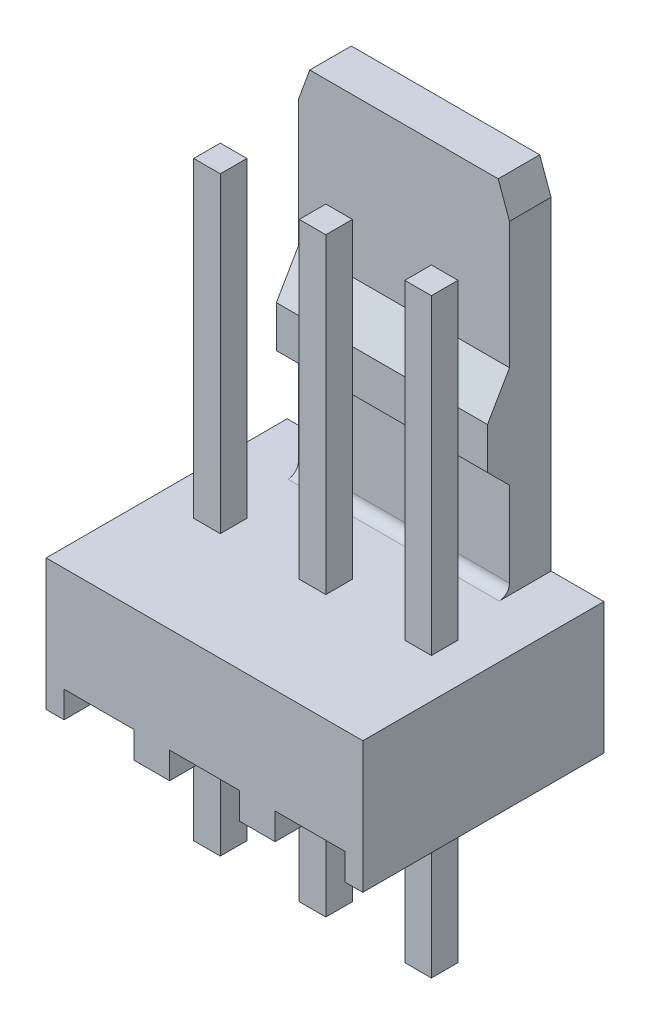
SolidWorks part; units mm, degrees
ref_plane "Front Plane" through (0, 0, 0) normal (0, 0, 1) x (1, 0, 0)
ref_plane "Top Plane" through (0, 0, 0) normal (0, 1, 0) x (1, 0, 0)
ref_plane "Right Plane" through (0, 0, 0) normal (1, 0, 0) x (0, 0, -1)
ref_plane "Plane1" through (0, -1.58, 0) normal (0, -1, 0) x (1, 0, 0)
sketch "Sketch1" plane through (0, -1.58, 0) normal (0, -1, 0) x (1, 0, 0)
  line L0 (3.81, -2.88) -> (3.81, 2.92)
  line L1 (3.81, 2.92) -> (-3.81, 2.92)
  line L2 (-3.81, 2.92) -> (-3.81, -2.88)
  line L3 (-3.81, -2.88) -> (3.81, -2.88)
extrude "Boss-Extrude1" add sketch "Sketch1" against normal blind 3.16
sketch "Sketch2" plane through (0, 1.58, 0) normal (0, 1, 0) x (-1, 0, 0)
  line L0 (2.54, -1.88) -> (2.54, -2.88)
  line L1 (2.54, -2.88) -> (-2.54, -2.88)
  line L2 (-2.54, -2.88) -> (-2.54, -1.88)
  line L3 (-2.54, -1.88) -> (2.54, -1.88)
extrude "Boss-Extrude2" add sketch "Sketch2" along normal blind 8.54
sketch "Sketch3" plane through (0, 0, -1.88) normal (0, 0, 1) x (1, 0, 0)
  line L0 (2.54, 10.12) -> (2.54, 3.87)
  line L1 (2.54, 3.87) -> (-2.54, 3.87)
  line L2 (-2.54, 3.87) -> (-2.54, 10.12)
  line L3 (-2.54, 10.12) -> (2.54, 10.12)
extrude "Boss-Extrude3" add sketch "Sketch3" along normal blind 0.53
sketch "Sketch4" plane through (0, 0, -2.88) normal (0, 0, -1) x (-1, 0, 0)
  line L0 (1.7, -1.58) -> (3.38, -1.58)
  line L1 (3.38, -1.58) -> (3.38, -0.94)
  line L2 (3.38, -0.94) -> (1.7, -0.94)
  line L3 (1.7, -0.94) -> (1.7, -1.58)
extrude "Cut-Extrude1" cut sketch "Sketch4" against normal through all
sketch "Sketch5" plane through (0, 0, -2.88) normal (0, 0, -1) x (-1, 0, 0)
  line L0 (-0.84, -1.58) -> (0.84, -1.58)
  line L1 (0.84, -1.58) -> (0.84, -0.94)
  line L2 (0.84, -0.94) -> (-0.84, -0.94)
  line L3 (-0.84, -0.94) -> (-0.84, -1.58)
extrude "Cut-Extrude2" cut sketch "Sketch5" against normal through all
sketch "Sketch6" plane through (2.54, 0, 0) normal (1, 0, 0) x (0, 0, -1)
  line L0 (1.35, 6.318) -> (1.88, 6.318)
  line L1 (1.88, 6.318) -> (1.88, 10.12)
  line L2 (1.88, 10.12) -> (1.35, 10.12)
  line L3 (1.35, 10.12) -> (1.35, 6.318)
extrude "Cut-Extrude3" cut sketch "Sketch6" against normal through all
sketch "Sketch7" plane through (0, 0, -2.88) normal (0, 0, -1) x (-1, 0, 0)
  line L0 (-3.38, -1.58) -> (-1.7, -1.58)
  line L1 (-1.7, -1.58) -> (-1.7, -0.94)
  line L2 (-1.7, -0.94) -> (-3.38, -0.94)
  line L3 (-3.38, -0.94) -> (-3.38, -1.58)
extrude "Cut-Extrude4" cut sketch "Sketch7" against normal through all
sketch "Sketch8" plane through (0, -0.94, 0) normal (0, -1, 0) x (1, 0, 0)
  line L0 (0.32, 0.32) -> (0.32, -0.32)
  line L1 (0.32, -0.32) -> (-0.32, -0.32)
  line L2 (-0.32, -0.32) -> (-0.32, 0.32)
  line L3 (-0.32, 0.32) -> (0.32, 0.32)
extrude "Boss-Extrude4" add sketch "Sketch8" along normal blind 4.2
sketch "Sketch9" plane through (0, -0.94, 0) normal (0, -1, 0) x (1, 0, 0)
  line L0 (-2.86, -0.32) -> (-2.86, 0.32)
  line L1 (-2.86, 0.32) -> (-2.22, 0.32)
  line L2 (-2.22, 0.32) -> (-2.22, -0.32)
  line L3 (-2.22, -0.32) -> (-2.86, -0.32)
extrude "Boss-Extrude5" add sketch "Sketch9" along normal blind 4.2
sketch "Sketch10" plane through (0, -0.94, 0) normal (0, -1, 0) x (1, 0, 0)
  line L0 (2.86, 0.32) -> (2.86, -0.315)
  line L1 (2.86, -0.315) -> (2.22, -0.315)
  line L2 (2.22, -0.315) -> (2.22, 0.32)
  line L3 (2.22, 0.32) -> (2.86, 0.32)
extrude "Boss-Extrude6" add sketch "Sketch10" along normal blind 4.2
sketch "Sketch11" plane through (0, 1.58, 0) normal (0, 1, 0) x (-1, 0, 0)
  line L0 (-0.32, -0.32) -> (-0.32, 0.32)
  line L1 (-0.32, 0.32) -> (0.32, 0.32)
  line L2 (0.32, 0.32) -> (0.32, -0.32)
  line L3 (0.32, -0.32) -> (-0.32, -0.32)
extrude "Boss-Extrude7" add sketch "Sketch11" along normal blind 7.5
sketch "Sketch12" plane through (0, 1.58, 0) normal (0, 1, 0) x (-1, 0, 0)
  line L0 (-2.86, -0.32) -> (-2.86, 0.32)
  line L1 (-2.86, 0.32) -> (-2.22, 0.32)
  line L2 (-2.22, 0.32) -> (-2.22, -0.32)
  line L3 (-2.22, -0.32) -> (-2.86, -0.32)
extrude "Boss-Extrude8" add sketch "Sketch12" along normal blind 7.5
sketch "Sketch13" plane through (0, 1.58, 0) normal (0, 1, 0) x (-1, 0, 0)
  line L0 (2.86, 0.32) -> (2.86, -0.32)
  line L1 (2.86, -0.32) -> (2.22, -0.32)
  line L2 (2.22, -0.32) -> (2.22, 0.32)
  line L3 (2.22, 0.32) -> (2.86, 0.32)
extrude "Boss-Extrude9" add sketch "Sketch13" along normal blind 7.5
draft "Draft1" type of draft neutral plane draft angle 45 faces to draft 1 face at (0, 3.87, -1.615) neutral plane through (2.54, 10.12, -1.88) neutral plane normal (0, 0, 1) parameters "D1"=45
draft "Draft2" type of draft neutral plane draft angle 60 faces to draft 1 face at (0, 6.318, -1.615) neutral plane through (-3.81, 6.318, -1.88) neutral plane normal (0, 0, 1) parameters "D1"=60
chamfer "Chamfer1" distance 0.75 angle 20 1 edges at (2.54, 10.12, -2.38)
chamfer "Chamfer2" distance 0.273 angle 70 1 edges at (-2.54, 10.12, -2.38)
fillet "Fillet1" radius 0.25 1 edges at (0, 1.58, -1.88)
sketch "Sketch14" plane through (0, -5.14, 0) normal (0, -1, 0) x (1, 0, 0)
  line L0 (2.86, 0.32) -> (2.22, -0.315) construction
  point P4 (2.54, 0.0025)
ref_plane "Plane2" through (2.54, 0, 0) normal (1, 0, 0) x (0, 0, -1)
sketch "Sketch15" plane through (2.54, 0, 0) normal (1, 0, 0) x (0, 0, -1)
  line L0 (-0.0025, -5.14) -> (-0.0025, -7.2145) construction
